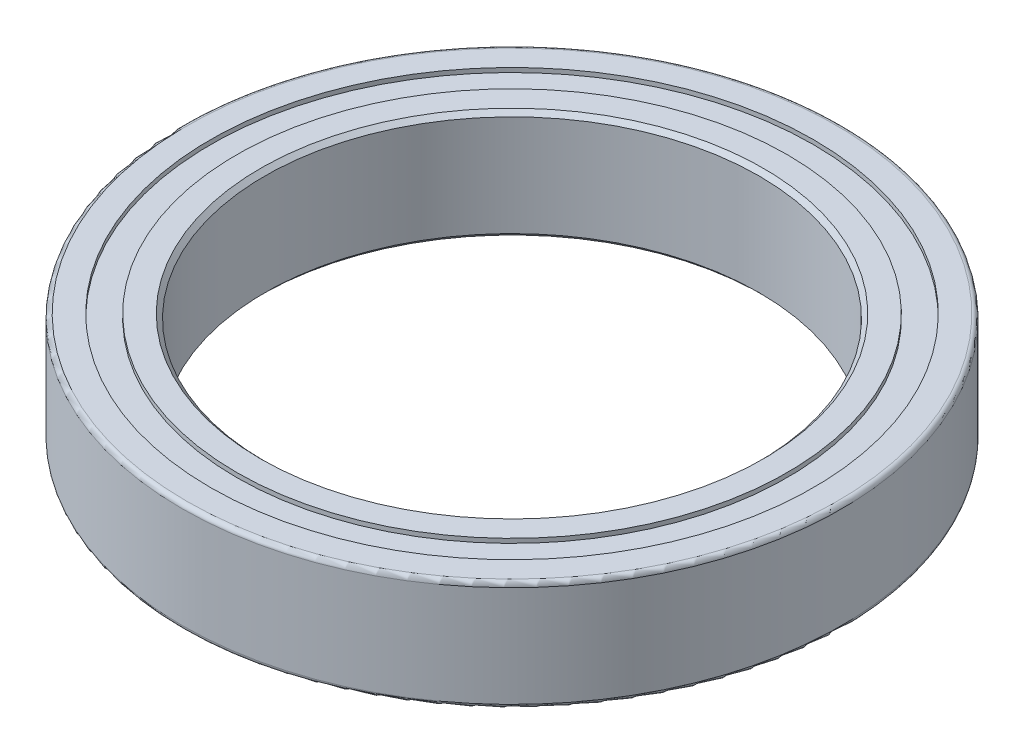
SolidWorks part; units mm, degrees
ref_plane "Front" through (0, 0, 0) normal (0, 0, 1) x (1, 0, 0)
ref_plane "Top" through (0, 0, 0) normal (0, 1, 0) x (1, 0, 0)
ref_plane "Right" through (0, 0, 0) normal (1, 0, 0) x (0, 0, -1)
sketch "Sketch1" plane through (0, 0, 0) normal (0, 1, 0) x (1, 0, 0)
  circle A0 centre (0, 0) radius 7.1438
  circle A1 centre (0, 0) radius 7.9566
  circle A2 centre (0, 0) radius 9.525
  circle A3 centre (0, 0) radius 8.7122
  dimension "D1" = 14.2875
  dimension "D3" = 19.05
  dimension "D2" = 0.8128
  dimension "D4" = 0.8128
extrude "Boss-Extrude1" add sketch "Sketch1" along normal mid plane 3.175 contours A2 A3 | A1 A0
fillet "Fillet1" radius 0.127 2 edges at (0, -1.5875, 9.525) (0, 1.5875, 9.525)
chamfer "Chamfer1" distance 0.127 2 edges at (0, -1.5875, 7.1438) (0, 1.5875, 7.1438)
sketch "Sketch2" plane through (0, 0, 0) normal (0, 1, 0) x (1, 0, 0)
  circle A0 centre (0, 0) radius 7.9566 construction
  circle A1 centre (0, 0) radius 8.7122 construction
  circle A2 centre (0, 0) radius 7.9566
  circle A3 centre (0, 0) radius 8.7122
extrude "Boss-Extrude2" add sketch "Sketch2" along normal mid plane 2.921 contours A3
equation "\"D1@Boss-Extrude2\"= \"D1@Boss-Extrude1\" - 0.01"
